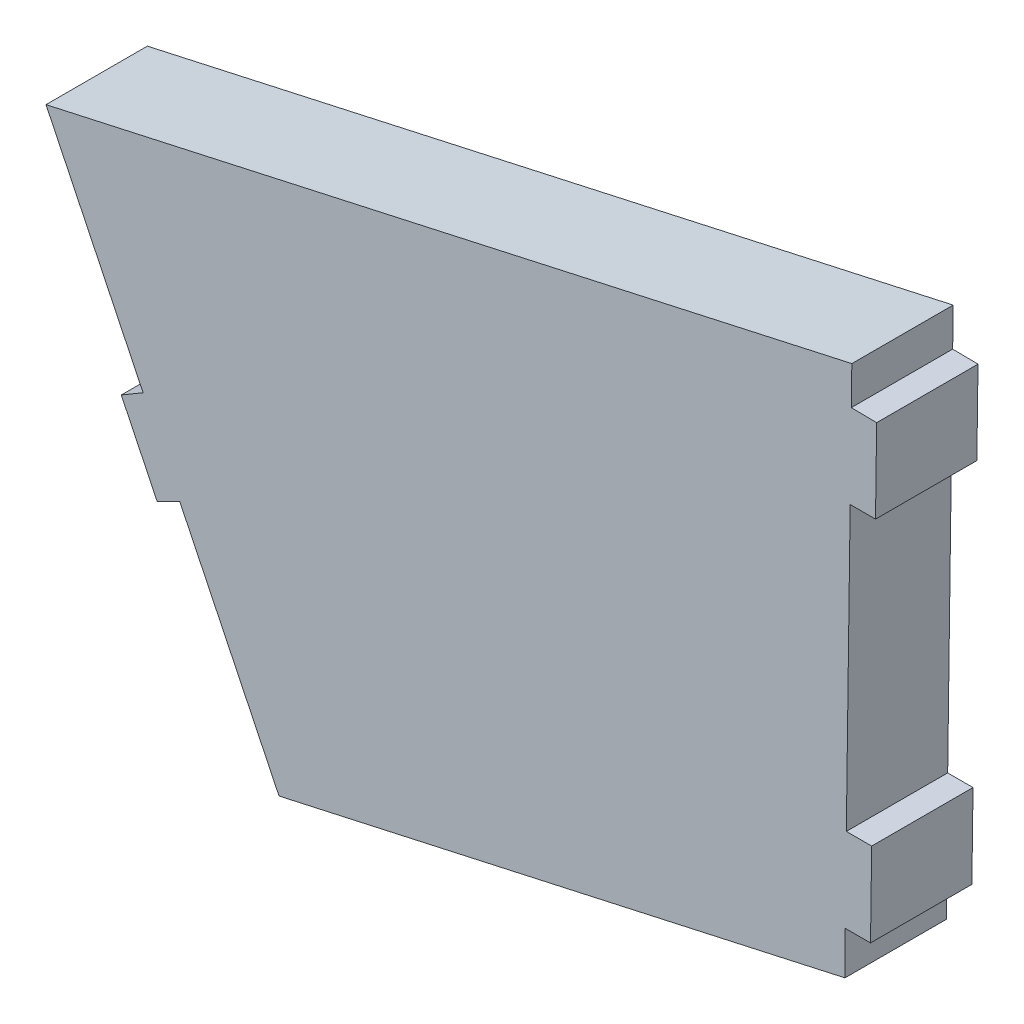
SolidWorks part; units mm, degrees
ref_plane "Front Plane" through (0, 0, 0) normal (0, 0, 1) x (1, 0, 0)
ref_plane "Top Plane" through (0, 0, 0) normal (0, 1, 0) x (1, 0, 0)
ref_plane "Right Plane" through (0, 0, 0) normal (1, 0, 0) x (0, 0, -1)
sketch "Sketch1" plane through (0, 0, 0) normal (0, 0, 1) x (1, 0, 0)
  line L0 (-4.9094, 101.4918) -> (-38.4112, 94.0647)
  line L1 (-38.4112, 94.0647) -> (-44.2822, 106.2148)
  line L2 (-44.2822, 106.2148) -> (-45.6281, 105.5644)
  line L3 (-45.6281, 105.5644) -> (-47.7494, 109.9542)
  line L4 (-47.7494, 109.9542) -> (-46.4576, 110.7167)
  line L5 (-46.4576, 110.7167) -> (-52.2054, 122.6118)
  line L6 (-52.2054, 122.6118) -> (-4.5034, 133.187)
  line L7 (-4.5034, 133.187) -> (-4.5341, 130.9138)
  line L8 (-4.5341, 130.9138) -> (-3.0344, 130.8935)
  line L9 (-3.0344, 130.8935) -> (-3.1016, 125.9142)
  line L10 (-3.1016, 125.9142) -> (-4.6016, 125.9142)
  line L11 (-4.6016, 125.9142) -> (-4.8294, 109.0407)
  line L12 (-4.8294, 109.0407) -> (-3.3294, 109.0407)
  line L13 (-3.3294, 109.0407) -> (-3.3969, 104.0411)
  line L14 (-3.3969, 104.0411) -> (-4.8969, 104.0411)
  line L15 (-4.8969, 104.0411) -> (-4.9094, 101.4918)
extrude "Boss-Extrude1" add sketch "Sketch1" along normal blind 6 contours L6 L7 L8 L9 L10 L11 L12 L13 L14 L15 L0 L1 L2 L3 L4 L5
